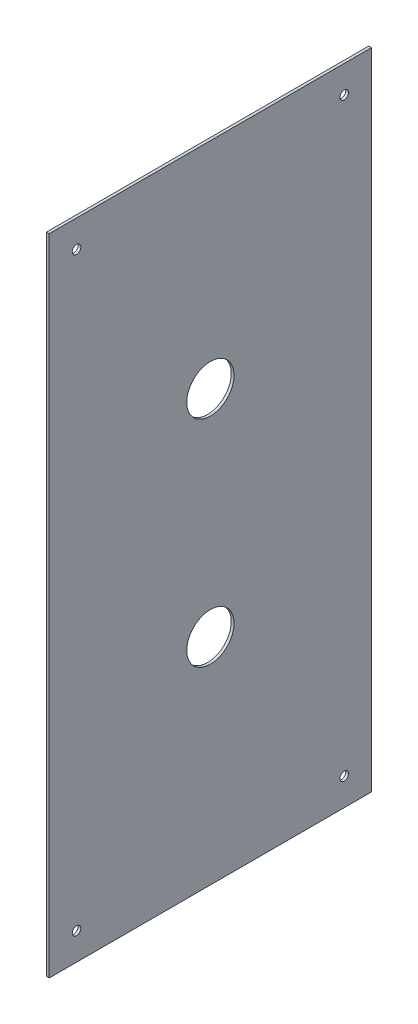
SolidWorks part; units mm, degrees
material "5052-H32"
ref_plane "Front Plane" through (0, 0, 0) normal (1, 0, 0) x (0, 1, 0)
ref_plane "Top Plane" through (0, 0, 0) normal (0, 0, 1) x (0, 1, 0)
ref_plane "Right Plane" through (0, 0, 0) normal (0, 1, 0) x (-1, 0, 0)
sketch "Sketch1" plane through (0, 0, 0) normal (1, 0, 0) x (0, 1, 0)
  line L1 (-150, -75) -> (150, -75)
  line L2 (-150, -75) -> (-150, 75)
  line L3 (-150, 75) -> (150, 75)
  line L4 (150, -75) -> (150, 75)
  line L5 (-150, -75) -> (150, 75) construction
  line L6 (-150, 75) -> (150, -75) construction
  point P0 (0, 0)
extrude "Boss-Extrude1" add sketch "Sketch1" along normal blind 1.3
hole_wizard "Ø4.0 (4) Diameter Hole1" positions "Sketch2" profile "Sketch3" hole size "Ø4.0" standard "ISO" end condition through all
sketch "Sketch2" plane through (1.3, 0, 0) normal (1, 0, 0) x (0, 1, 0)
  line L0 (-150, 75) -> (-150, -75) construction
  line L1 (150, 75) -> (-150, 75) construction
  point P0 (-137.3, 62.3)
  dimension "D1" = 12.7
  dimension "D2" = 12.7
sketch "Sketch3" plane through (1.3, -137.3, 62.3) normal (0, 1, 0) x (0, 0, -1)
  line L0 (0, 0) -> (0, 1.3)
  line L1 (0, 1.3) -> (2, 1.3)
  line L2 (2, 1.3) -> (2, 0)
  line L5 (2, 0) -> (0, 0)
  line L11 (0, -6.35) -> (0, 107.95) construction
  dimension "Thru Hole Dia." = 4
  dimension "Thru Hole Depth" = 1.3
mirror "Mirror1" about plane through (0, 0, 0) normal (0, 1, 0) of "Ø4.0 (4) Diameter Hole1" second plane through (0, 0, 0) second plane normal (0, 0, 1)
hole_wizard "Ø22.0 (22) Diameter Hole1" positions "Sketch4" profile "Sketch5" hole size "Ø22.0" standard "ISO" end condition through all
sketch "Sketch4" plane through (1.3, 0, 0) normal (1, 0, 0) x (0, 1, 0)
  point P0 (-50, 0)
  dimension "D1" = 50
sketch "Sketch5" plane through (1.3, -50, 0) normal (0, 1, 0) x (0, 0, -1)
  line L0 (0, 0) -> (0, 1.3)
  line L1 (0, 1.3) -> (11, 1.3)
  line L2 (11, 1.3) -> (11, 0)
  line L5 (11, 0) -> (0, 0)
  line L11 (0, -6.35) -> (0, 107.95) construction
  dimension "Thru Hole Dia." = 22
  dimension "Thru Hole Depth" = 1.3
mirror "Mirror2" about plane through (0, 0, 0) normal (0, 1, 0) of "Ø22.0 (22) Diameter Hole1"
